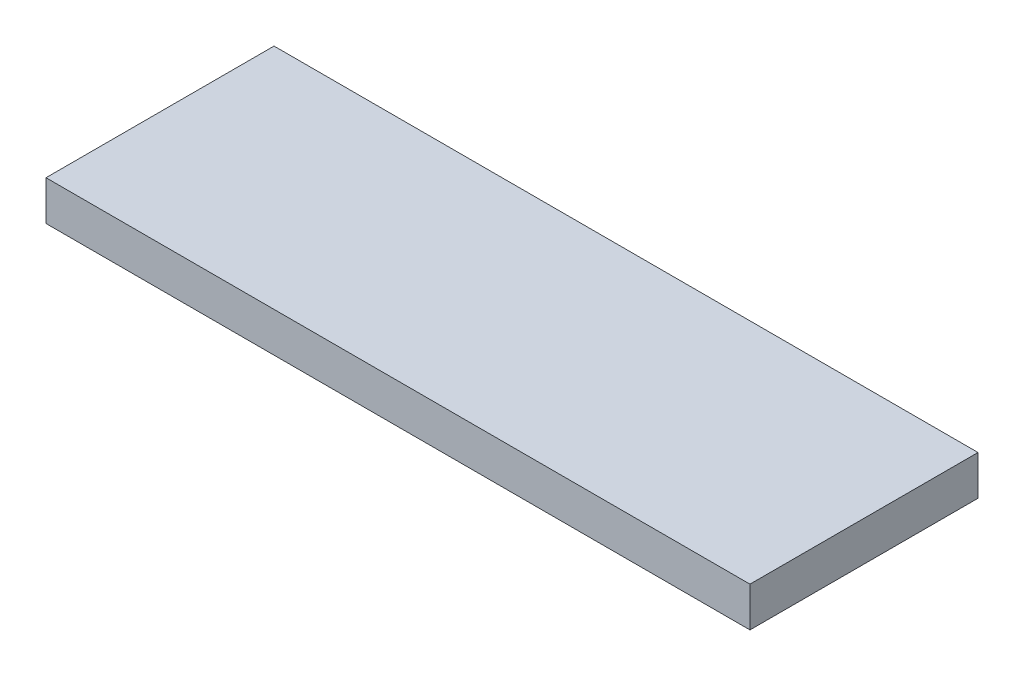
SolidWorks part; units mm, degrees
ref_plane "Front Plane" through (0, 0, 0) normal (0, 0, 1) x (1, 0, 0)
ref_plane "Top Plane" through (0, 0, 0) normal (0, 1, 0) x (1, 0, 0)
ref_plane "Right Plane" through (0, 0, 0) normal (1, 0, 0) x (0, 0, -1)
sketch "Sketch1" plane through (0, 0, 0) normal (0, 1, 0) x (1, 0, 0)
  line L1 (-29.8882, 3.7873) -> (5.6118, 3.7873)
  line L2 (-29.8882, 3.7873) -> (-29.8882, -7.7127)
  line L3 (-29.8882, -7.7127) -> (5.6118, -7.7127)
  line L4 (5.6118, 3.7873) -> (5.6118, -7.7127)
  dimension "D1" = 11.5
  dimension "D2" = 35.5
extrude "Boss-Extrude1" add sketch "Sketch1" along normal blind 2
scale "Scale1" scale about centroid uniform scaling yes scale factor 10
